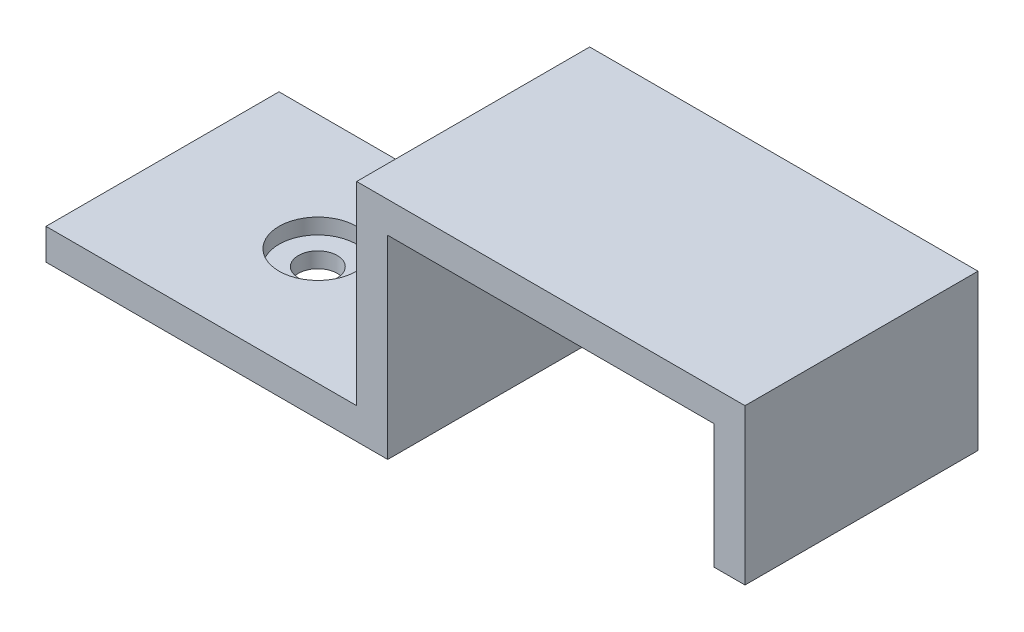
SolidWorks part; units mm, degrees
ref_plane "Front Plane" through (0, 0, 0) normal (0, 0, 1) x (1, 0, 0)
ref_plane "Top Plane" through (0, 0, 0) normal (0, 1, 0) x (1, 0, 0)
ref_plane "Right Plane" through (0, 0, 0) normal (1, 0, 0) x (0, 0, -1)
sketch "Sketch1" plane through (0, 0, 0) normal (0, 1, 0) x (1, 0, 0)
  line L1 (-20, 15) -> (20, 15)
  line L2 (-20, 15) -> (-20, -15)
  line L3 (-20, -15) -> (20, -15)
  line L4 (20, 15) -> (20, -15)
  line L5 (-20, 15) -> (20, -15) construction
  line L6 (-20, -15) -> (20, 15) construction
  point P0 (0, 0)
  dimension "D1" = 40
  dimension "D2" = 30
extrude "Boss-Extrude1" add sketch "Sketch1" along normal blind 4
sketch "Sketch2" plane through (0, 4, 0) normal (0, 1, 0) x (1, 0, 0)
  circle A0 centre (0, 0) radius 2.5
  dimension "D1" = 5
extrude "Cut-Extrude1" cut sketch "Sketch2" against normal through all
sketch "Sketch3" plane through (0, 4, 0) normal (0, 1, 0) x (1, 0, 0)
  circle A0 centre (0, 0) radius 5
  dimension "D1" = 10
extrude "Cut-Extrude2" cut sketch "Sketch3" against normal blind 2
sketch "Sketch4" plane through (0, 0, -15) normal (0, 0, -1) x (-1, 0, 0)
  line L1 (-20, 0) -> (-24, 0)
  line L2 (-20, 0) -> (-20, 25)
  line L3 (-20, 25) -> (-24, 25)
  line L4 (-24, 0) -> (-24, 25)
  line L9 (-20, 25) -> (-66, 25)
  line L10 (-20, 25) -> (-20, 29)
  line L11 (-20, 29) -> (-66, 29)
  line L12 (-66, 25) -> (-66, 29)
  line L13 (-66, 29) -> (-70, 29)
  line L14 (-66, 29) -> (-66, 9)
  line L15 (-66, 9) -> (-70, 9)
  line L16 (-70, 29) -> (-70, 9)
  line M12 (-20, 4) -> (-20, 0)
  dimension "D1" = 25
  dimension "D2" = 4
  dimension "D3" = 42
  dimension "D4" = 4
  dimension "D5" = 20
  dimension "D6" = 4
extrude "Boss-Extrude2" add sketch "Sketch4" against normal up to surface (30 mm away) contours L4 L1 L2 L3 M12 | L12 L9 L3 L10 L11 | L13 L16 L15 L14 L12 up to face at (0, 2, 15)
